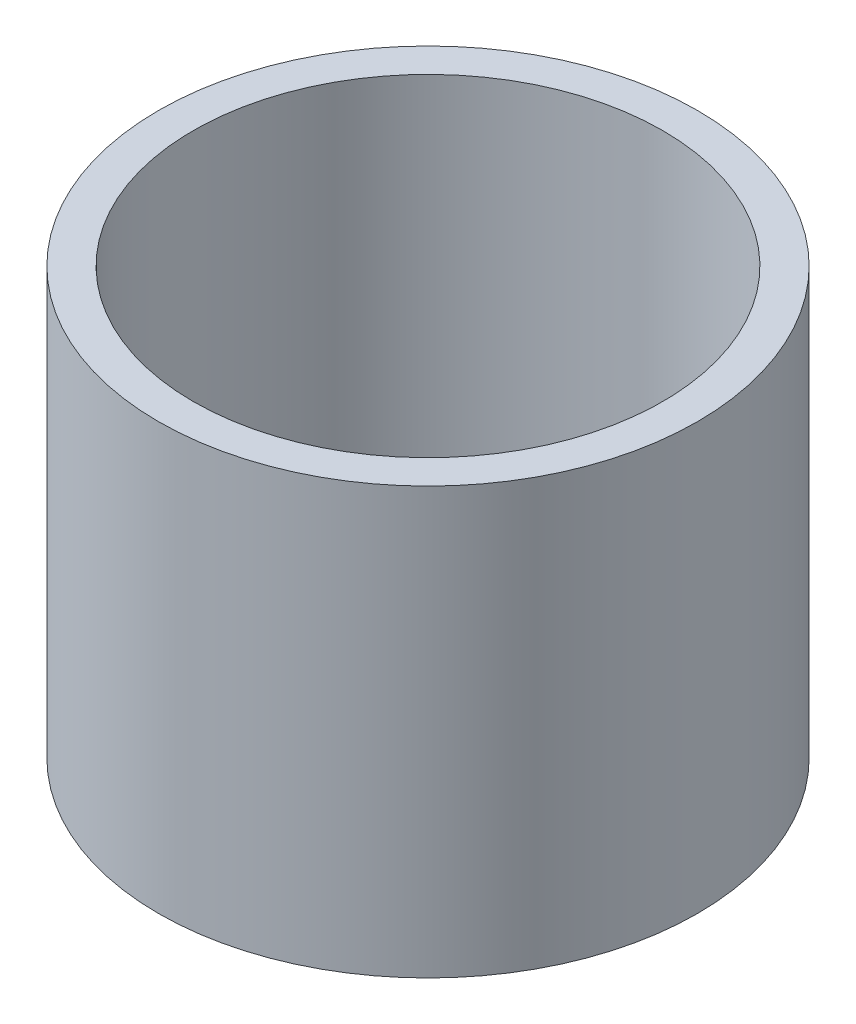
SolidWorks part; units mm, degrees
ref_plane "Ön Düzlem" through (0, 0, 0) normal (0, 0, 1) x (1, 0, 0)
ref_plane "Üst Düzlem" through (0, 0, 0) normal (0, 1, 0) x (1, 0, 0)
ref_plane "Sağ Düzlem" through (0, 0, 0) normal (1, 0, 0) x (0, 0, -1)
sketch "Sketch1" plane through (0, 0, 0) normal (0, 1, 0) x (1, 0, 0)
  circle A0 centre (0, 0) radius 135
  circle A1 centre (0, 0) radius 155
extrude "Boss-Extrude1" add sketch "Sketch1" along normal blind 245
